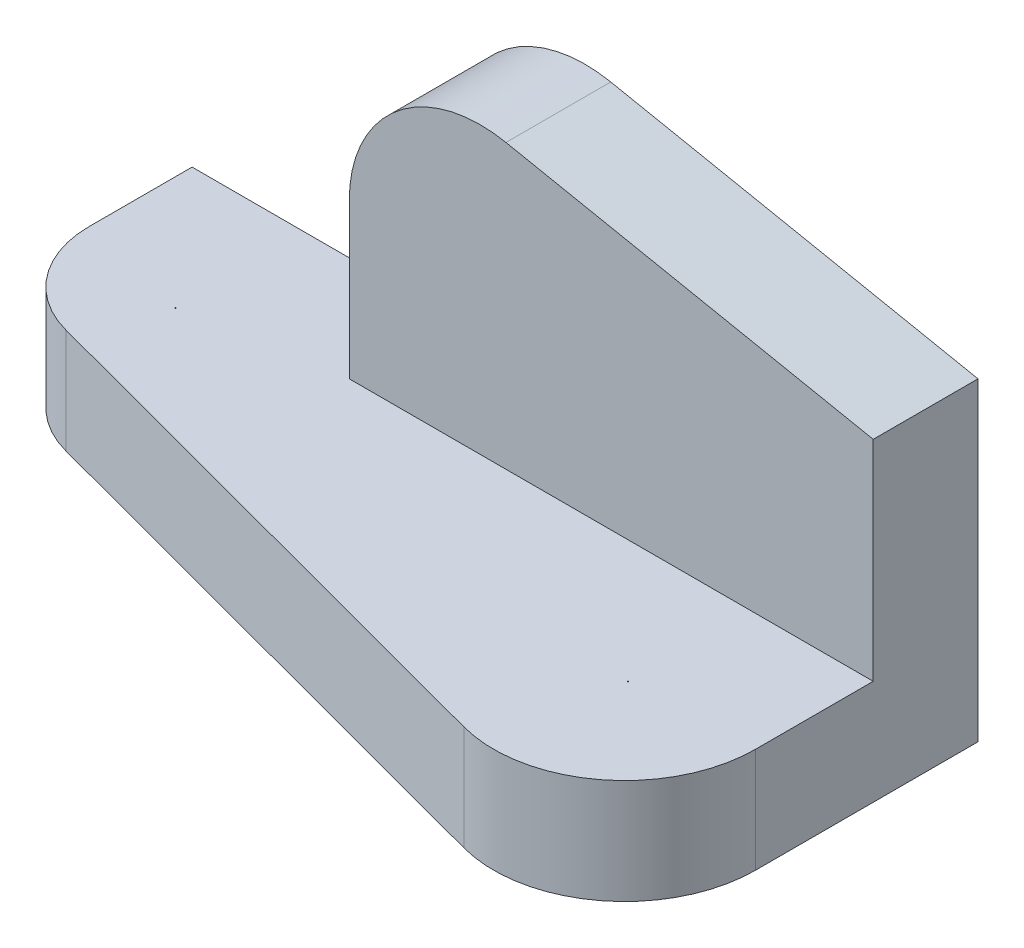
SolidWorks part; units mm, degrees
ref_plane "Front Plane" through (0, 0, 0) normal (0, 0, 1) x (1, 0, 0)
ref_plane "Top Plane" through (0, 0, 0) normal (0, 1, 0) x (1, 0, 0)
ref_plane "Right Plane" through (0, 0, 0) normal (1, 0, 0) x (0, 0, -1)
sketch "Sketch1" plane through (0, 0, 0) normal (0, 1, 0) x (1, 0, 0)
  line L0 (0, 0) -> (0, 35)
  line L1 (0, 35) -> (150, 35)
  line L2 (150, 35) -> (150, -40)
  line L3 (150, -40) -> (0, 0)
  dimension "D1" = 35
  dimension "D2" = 150
  dimension "D3" = 75
extrude "Boss-Extrude1" add sketch "Sketch1" along normal blind 20 contours L1 L2 L3 L0
sketch "Sketch3" plane through (0, 0, -35) normal (0, 0, -1) x (-1, 0, 0)
  line L0 (-150, 0) -> (-150, 60)
  line L1 (-150, 60) -> (-50, 80)
  line L2 (-50, 80) -> (-50, 0)
  line L3 (0, 0) -> (-150, 0) construction
  line L4 (-50, 0) -> (-150, 0)
  dimension "D1" = 80
  dimension "D2" = 60
  dimension "10" = 100
extrude "Boss-Extrude2" add sketch "Sketch3" against normal blind 20
fillet "Fillet1" radius 20 1 edges at (0, 10, 0)
fillet "Fillet2" radius 25 2 edges at (150, 10, 40) (50, 80, -25)
hole_wizard "Ø0.2 (0.2) Diameter Hole1" positions "3DSketch1" profile "Sketch4" hole size "Ø0.2" standard "AS" end condition through all
sketch3d "3DSketch1"
  point P0 (21.6997, 20, -10.1409)
  point P2 (126.6175, 20, 8.4446)
sketch "Sketch4" plane through (21.6997, 20, -10.1409) normal (1, 0, 0) x (0, 0, 1)
  line L0 (0, 0) -> (0, 20)
  line L1 (0, 20) -> (0.1, 20)
  line L2 (0.1, 20) -> (0.1, 0)
  line L5 (0.1, 0) -> (0, 0)
  line L11 (0, -6.35) -> (0, 107.95) construction
  dimension "Thru Hole Dia." = 0.2
  dimension "Thru Hole Depth" = 20
